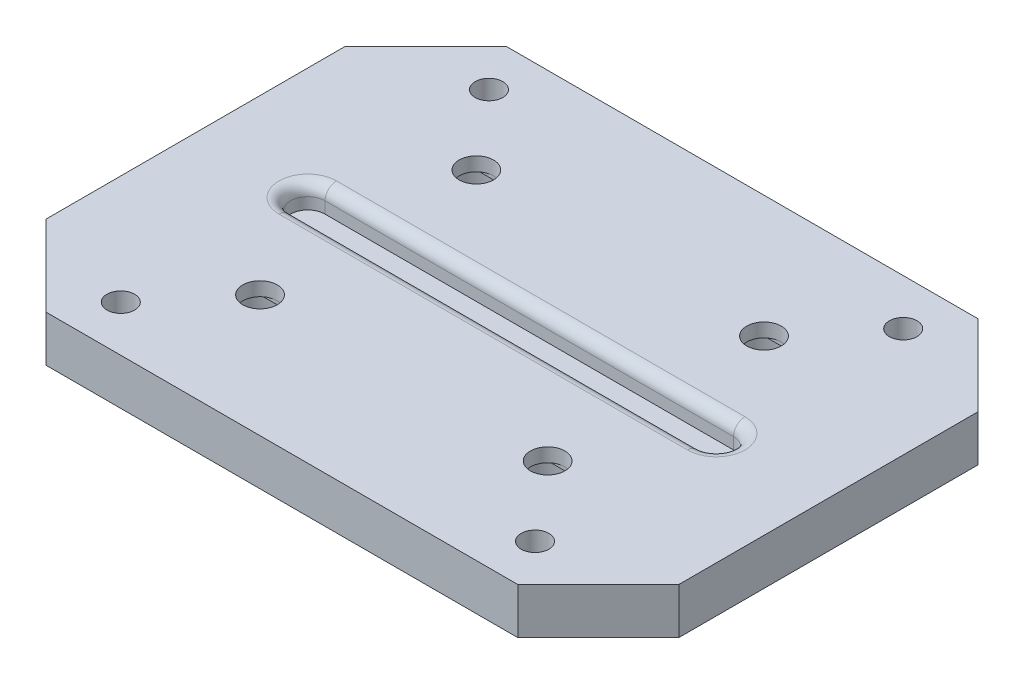
SolidWorks part; units mm, degrees
ref_plane "Front Plane" through (0, 0, 0) normal (0, 0, 1) x (1, 0, 0)
ref_plane "Top Plane" through (0, 0, 0) normal (0, 1, 0) x (1, 0, 0)
ref_plane "Right Plane" through (0, 0, 0) normal (1, 0, 0) x (0, 0, -1)
sketch "Sketch1" plane through (0, 0, 0) normal (0, 1, 0) x (1, 0, 0)
  line L0 (-12.5, 9.4) -> (12.5, 9.4) construction
  line L1 (-12.5, -9.4) -> (12.5, -9.4) construction
  line L2 (-17.75, 0) -> (17.75, 0) construction
  line L3 (0, 9.4) -> (0, -9.4) construction
  line L36 (-12.5, -10.9) -> (12.5, -10.9)
  line L37 (12.5, -7.9) -> (-12.5, -7.9)
  line L40 (12.5, 10.9) -> (-12.5, 10.9)
  line L41 (-12.5, 7.9) -> (12.5, 7.9)
  line L84 (-17.75, -1.5) -> (17.75, -1.5)
  line L85 (17.75, 1.5) -> (-17.75, 1.5)
  arc A36 (12.5, -10.9) -> (12.5, -7.9) centre (12.5, -9.4) ccw
  arc A37 (-12.5, -7.9) -> (-12.5, -10.9) centre (-12.5, -9.4) ccw
  arc A40 (-12.5, 10.9) -> (-12.5, 7.9) centre (-12.5, 9.4) ccw
  arc A41 (12.5, 7.9) -> (12.5, 10.9) centre (12.5, 9.4) ccw
  arc A90 (17.75, -1.5) -> (17.75, 1.5) centre (17.75, 0) ccw
  arc A91 (-17.75, 1.5) -> (-17.75, -1.5) centre (-17.75, 0) ccw
  point P10 (0, 0)
  point P15 (0, 0)
  dimension "D3" = 1.5
  dimension "D1" = 25
  dimension "D2" = 35.5
  dimension "D4" = 18.8
sketch "Sketch2" plane through (0, 0, 0) normal (0, 1, 0) x (1, 0, 0)
  line L0 (0, -14) -> (0, 14) construction
  line L1 (-904.7843, 14) -> (44334.4284, 14) construction
  line L2 (-910.7454, -14) -> (44328.4673, -14) construction
  line L3 (-16, 0) -> (16, 0) construction
  line L4 (16, -904.7843) -> (16, 44334.4284) construction
  line L5 (-16, -896.2279) -> (-16, 44342.9847) construction
  line L7 (-27.5, -20) -> (27.5, -20)
  line L8 (-27.5, -20) -> (-27.5, 20)
  line L9 (-27.5, 20) -> (27.5, 20)
  line L10 (27.5, -20) -> (27.5, 20)
  line L11 (-27.5, -20) -> (27.5, 20) construction
  line L12 (-27.5, 20) -> (27.5, -20) construction
  line L14 (12.5, 10.9) -> (-12.5, 10.9)
  line L15 (-12.5, 7.9) -> (12.5, 7.9)
  line L16 (12.5, 10.9) -> (-12.5, 10.9) construction
  line L17 (-12.5, 7.9) -> (12.5, 7.9) construction
  line L18 (12.5, -7.9) -> (-12.5, -7.9)
  line L19 (-12.5, -10.9) -> (12.5, -10.9)
  line L20 (12.5, -7.9) -> (-12.5, -7.9) construction
  line L21 (-12.5, -10.9) -> (12.5, -10.9) construction
  line L22 (17.75, 1.5) -> (-17.75, 1.5)
  line L23 (-17.75, -1.5) -> (17.75, -1.5)
  line L24 (17.75, 1.5) -> (-17.75, 1.5) construction
  line L25 (-17.75, -1.5) -> (17.75, -1.5) construction
  circle A0 centre (18, 16) radius 2 construction
  circle A1 centre (-18, 16) radius 2 construction
  circle A2 centre (-18, -16) radius 2 construction
  circle A3 centre (18, -16) radius 2 construction
  circle A4 centre (-18, -16) radius 1.2
  circle A5 centre (18, -16) radius 1.2
  arc A6 (-12.5, 10.9) -> (-12.5, 7.9) centre (-12.5, 9.4) ccw
  arc A7 (12.5, 7.9) -> (12.5, 10.9) centre (12.5, 9.4) ccw
  arc A8 (-12.5, 10.9) -> (-12.5, 7.9) centre (-12.5, 9.4) ccw construction
  arc A9 (12.5, 7.9) -> (12.5, 10.9) centre (12.5, 9.4) ccw construction
  arc A10 (-12.5, -7.9) -> (-12.5, -10.9) centre (-12.5, -9.4) ccw
  arc A11 (12.5, -10.9) -> (12.5, -7.9) centre (12.5, -9.4) ccw
  arc A12 (-12.5, -7.9) -> (-12.5, -10.9) centre (-12.5, -9.4) ccw construction
  arc A13 (12.5, -10.9) -> (12.5, -7.9) centre (12.5, -9.4) ccw construction
  arc A14 (-17.75, 1.5) -> (-17.75, -1.5) centre (-17.75, 0) ccw
  arc A15 (17.75, -1.5) -> (17.75, 1.5) centre (17.75, 0) ccw
  arc A16 (-17.75, 1.5) -> (-17.75, -1.5) centre (-17.75, 0) ccw construction
  arc A17 (17.75, -1.5) -> (17.75, 1.5) centre (17.75, 0) ccw construction
  circle A18 centre (-18, 16) radius 1.2
  circle A19 centre (18, 16) radius 1.2
  point P2 (0, 0)
  point P10 (0, 0)
  point P23 (0, 0)
  dimension "D3" = 4
  dimension "D9" = 2.4
  dimension "D1" = 32
  dimension "D2" = 28
  dimension "D4" = 55
  dimension "D5" = 40
  dimension "D6" = 0
  dimension "D7" = 0
  dimension "D8" = 0
extrude "Boss-Extrude1" add sketch "Sketch2" against normal blind 4
chamfer "Chamfer1" distance 7 angle 45 4 edges at (-27.5, -2, 20) (27.5, -2, 20) (27.5, -2, -20) (-27.5, -2, -20)
ref_plane "Plane1" through (0, -2, 0) normal (0, 1, 0) x (1, 0, 0)
sketch "Sketch3" plane through (0, -2, 0) normal (0, 1, 0) x (1, 0, 0)
  line L2 (12.5, 10.9) -> (-12.5, 10.9)
  line L3 (-12.5, 7.9) -> (12.5, 7.9)
  line L4 (12.5, 10.9) -> (-12.5, 10.9) construction
  line L5 (-12.5, 7.9) -> (12.5, 7.9) construction
  line L6 (-12.5, -10.9) -> (12.5, -10.9)
  line L7 (12.5, -7.9) -> (-12.5, -7.9)
  line L8 (-12.5, -10.9) -> (12.5, -10.9) construction
  line L9 (12.5, -7.9) -> (-12.5, -7.9) construction
  line L10 (17.75, 1.5) -> (-17.75, 1.5)
  line L11 (-17.75, -1.5) -> (17.75, -1.5)
  line L12 (17.75, 1.5) -> (-17.75, 1.5)
  line L13 (-17.75, -1.5) -> (17.75, -1.5)
  circle A0 centre (12.5, 9.4) radius 1.5
  circle A1 centre (-12.5, 9.4) radius 1.5
  arc A2 (-12.5, 10.9) -> (-12.5, 7.9) centre (-12.5, 9.4) ccw
  arc A3 (12.5, 7.9) -> (12.5, 10.9) centre (12.5, 9.4) ccw
  arc A4 (-12.5, 10.9) -> (-12.5, 7.9) centre (-12.5, 9.4) ccw construction
  arc A5 (12.5, 7.9) -> (12.5, 10.9) centre (12.5, 9.4) ccw construction
  arc A6 (12.5, -10.9) -> (12.5, -7.9) centre (12.5, -9.4) ccw
  arc A7 (-12.5, -7.9) -> (-12.5, -10.9) centre (-12.5, -9.4) ccw
  arc A8 (12.5, -10.9) -> (12.5, -7.9) centre (12.5, -9.4) ccw construction
  arc A9 (-12.5, -7.9) -> (-12.5, -10.9) centre (-12.5, -9.4) ccw construction
  arc A10 (17.75, -1.5) -> (17.75, 1.5) centre (17.75, 0) ccw
  arc A11 (-17.75, 1.5) -> (-17.75, -1.5) centre (-17.75, 0) ccw
  arc A12 (17.75, -1.5) -> (17.75, 1.5) centre (17.75, 0) ccw
  arc A13 (-17.75, 1.5) -> (-17.75, -1.5) centre (-17.75, 0) ccw
  circle A14 centre (-12.5, -9.4) radius 1.5
  circle A15 centre (12.5, -9.4) radius 1.5
  dimension "D4" = 3
  dimension "D1" = 0
  dimension "D2" = 0
  dimension "D3" = 0
extrude "Cut-Extrude1" cut sketch "Sketch3" along normal through all
fillet "Fillet1" radius 1 4 edges at (19.25, 0, 0) (0, 0, 1.5) (-19.25, 0, 0) (0, 0, -1.5)
sketch "Sketch4" plane through (0, -2, 0) normal (0, 1, 0) x (1, 0, 0)
  line L2 (12.5, 10.9) -> (-12.5, 10.9)
  line L3 (-12.5, 7.9) -> (12.5, 7.9)
  line L4 (12.5, 10.9) -> (-12.5, 10.9) construction
  line L5 (-12.5, 7.9) -> (12.5, 7.9) construction
  line L6 (-12.5, -10.9) -> (12.5, -10.9)
  line L7 (12.5, -7.9) -> (-12.5, -7.9)
  line L8 (-12.5, -10.9) -> (12.5, -10.9) construction
  line L9 (12.5, -7.9) -> (-12.5, -7.9) construction
  line L10 (17.75, 1.5) -> (-17.75, 1.5)
  line L11 (-17.75, -1.5) -> (17.75, -1.5)
  line L12 (17.75, 1.5) -> (-17.75, 1.5) construction
  line L13 (-17.75, -1.5) -> (17.75, -1.5) construction
  circle A0 centre (-12.5, 9.4) radius 2.5
  circle A1 centre (12.5, 9.4) radius 2.5
  arc A2 (-12.5, 10.9) -> (-12.5, 7.9) centre (-12.5, 9.4) ccw
  arc A3 (12.5, 7.9) -> (12.5, 10.9) centre (12.5, 9.4) ccw
  arc A4 (-12.5, 10.9) -> (-12.5, 7.9) centre (-12.5, 9.4) ccw construction
  arc A5 (12.5, 7.9) -> (12.5, 10.9) centre (12.5, 9.4) ccw construction
  arc A6 (12.5, -10.9) -> (12.5, -7.9) centre (12.5, -9.4) ccw
  arc A7 (-12.5, -7.9) -> (-12.5, -10.9) centre (-12.5, -9.4) ccw
  arc A8 (12.5, -10.9) -> (12.5, -7.9) centre (12.5, -9.4) ccw construction
  arc A9 (-12.5, -7.9) -> (-12.5, -10.9) centre (-12.5, -9.4) ccw construction
  arc A10 (17.75, -1.5) -> (17.75, 1.5) centre (17.75, 0) ccw
  arc A11 (-17.75, 1.5) -> (-17.75, -1.5) centre (-17.75, 0) ccw
  arc A12 (17.75, -1.5) -> (17.75, 1.5) centre (17.75, 0) ccw construction
  arc A13 (-17.75, 1.5) -> (-17.75, -1.5) centre (-17.75, 0) ccw construction
  circle A14 centre (-12.5, -9.4) radius 2.5
  circle A15 centre (12.5, -9.4) radius 2.5
  dimension "D4" = 5
  dimension "D1" = 0
  dimension "D2" = 0
  dimension "D3" = 0
extrude "Cut-Extrude2" cut sketch "Sketch4" against normal through all from offset 0.5
sketch "Sketch5" plane through (0, -1.5, 0) normal (0, 1, 0) x (1, 0, 0)
  line L0 (-14.5, -10.9) -> (-10.5, -10.9)
  line L1 (-14.5, -7.9) -> (-10.5, -7.9)
  line L2 (-14.5, 7.9) -> (-10.5, 7.9)
  line L3 (-14.5, 10.9) -> (-10.5, 10.9)
  line L4 (10.5, -10.9) -> (14.5, -10.9)
  line L5 (10.5, -7.9) -> (14.5, -7.9)
  line L6 (10.5, 7.9) -> (14.5, 7.9)
  line L7 (10.5, 10.9) -> (14.5, 10.9)
  circle A0 centre (-12.5, -9.4) radius 1.5 construction
  circle A1 centre (-12.5, 9.4) radius 2.5
  arc A2 (-14.5, 10.9) -> (-14.5, 7.9) centre (-12.5, 9.4) ccw
  circle A3 centre (12.5, -9.4) radius 2.5
  arc A4 (10.5, -7.9) -> (10.5, -10.9) centre (12.5, -9.4) ccw
  circle A5 centre (-12.5, -9.4) radius 2.5
  arc A6 (-10.5, -10.9) -> (-10.5, -7.9) centre (-12.5, -9.4) ccw
  circle A7 centre (12.5, 9.4) radius 2.5
  arc A8 (14.5, 7.9) -> (14.5, 10.9) centre (12.5, 9.4) ccw
  circle A9 centre (12.5, -9.4) radius 1.5 construction
  circle A10 centre (12.5, 9.4) radius 1.5 construction
  circle A11 centre (-12.5, 9.4) radius 1.5 construction
  arc A12 (-14.5, -7.9) -> (-14.5, -10.9) centre (-12.5, -9.4) ccw
  arc A13 (14.5, -10.9) -> (14.5, -7.9) centre (12.5, -9.4) ccw
  arc A14 (-10.5, 7.9) -> (-10.5, 10.9) centre (-12.5, 9.4) ccw
  arc A15 (10.5, 10.9) -> (10.5, 7.9) centre (12.5, 9.4) ccw
  dimension "D1" = 0
  dimension "D2" = 0
  dimension "D3" = 0
  dimension "D4" = 0
extrude "Cut-Extrude6" cut sketch "Sketch5" along normal blind 0.3
